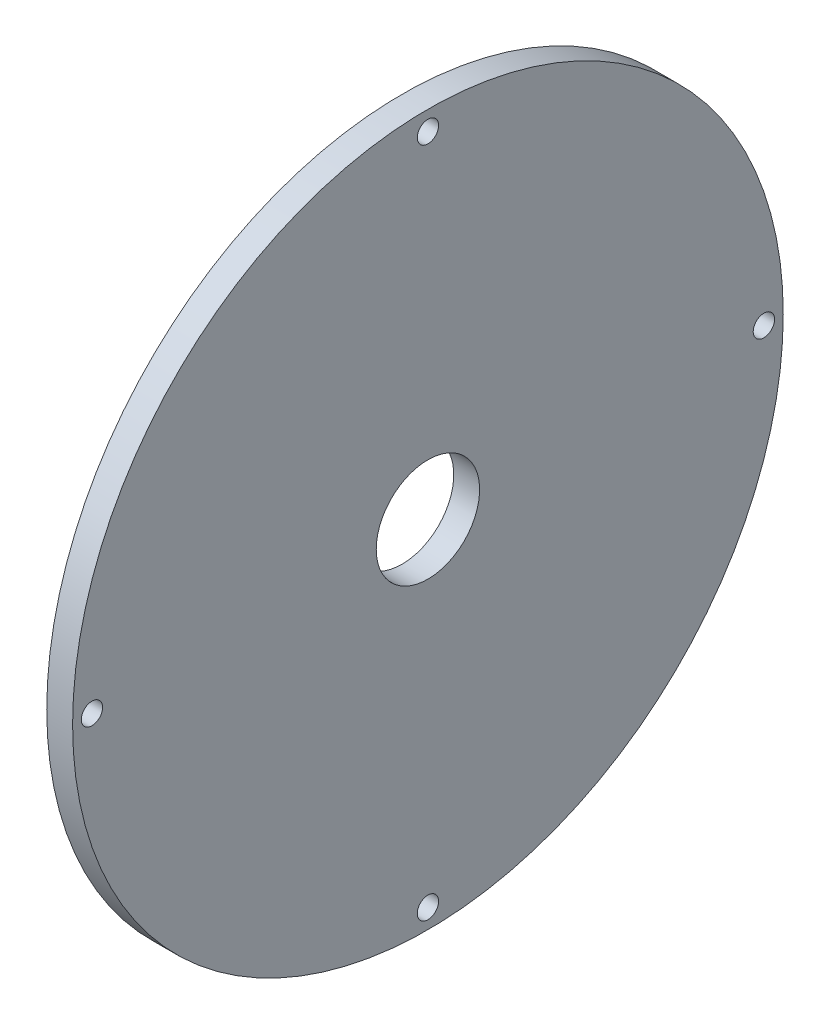
SolidWorks part; units mm, degrees
material "AISI 304"
ref_plane "Front Plane" through (0, 0, 0) normal (0, 0, 1) x (1, 0, 0)
ref_plane "Top Plane" through (0, 0, 0) normal (0, 1, 0) x (1, 0, 0)
ref_plane "Right Plane" through (0, 0, 0) normal (1, 0, 0) x (0, 0, -1)
sketch "Axial profile (mm)" plane through (0, 0, 0) normal (0, 0, 1) x (1, 0, 0)
  line L0 (-110, 0) -> (75, 0) construction
  line L1 (-130, 8) -> (-126, 8)
  line L2 (-126, 8) -> (-126, 55)
  line L3 (-126, 55) -> (-130, 55)
  line L4 (-130, 55) -> (-130, 8)
revolve "Full revolution" add sketch "Axial profile (mm)" angle 360 about L0
sketch "Sketch2" plane through (0, 0, 0) normal (1, 0, 0) x (0, 0, -1)
  circle A0 centre (0, 52) radius 1.65
  circle A1 centre (-52, 0) radius 1.65
  circle A2 centre (0, -52) radius 1.65
  circle A3 centre (52, 0) radius 1.65
extrude "Axial holes" cut sketch "Sketch2" along normal through all and the other way through all
